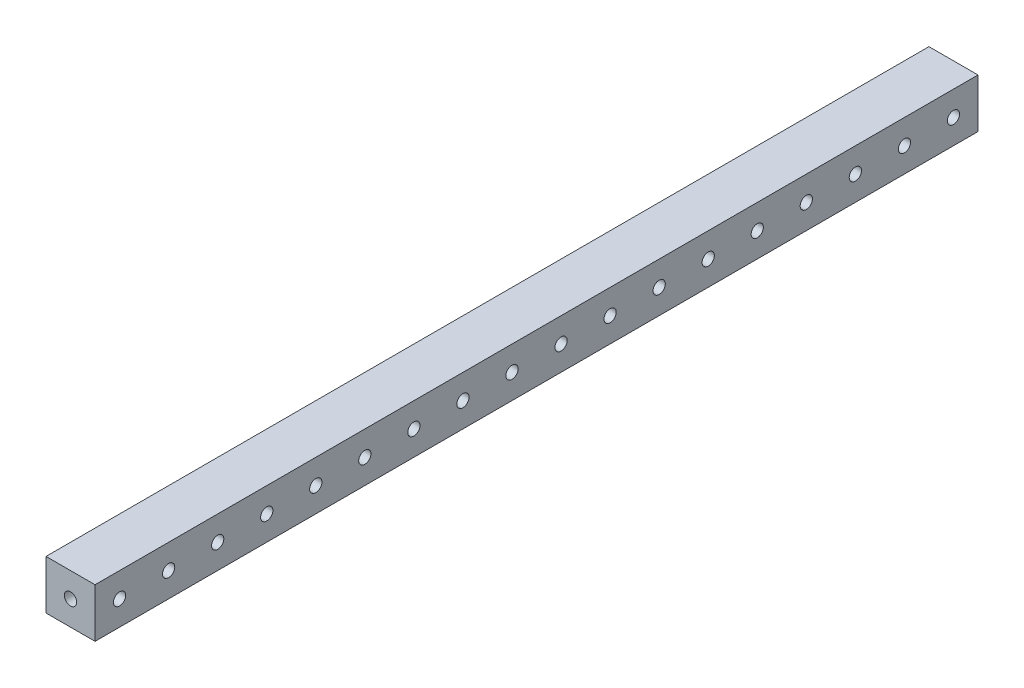
SolidWorks part; units mm, degrees
material "Pine"
ref_plane "Front Plane" through (0, 0, 0) normal (0, 0, 1) x (1, 0, 0)
ref_plane "Top Plane" through (0, 0, 0) normal (0, 1, 0) x (1, 0, 0)
ref_plane "Right Plane" through (0, 0, 0) normal (1, 0, 0) x (0, 0, -1)
sketch "Sketch1" plane through (0, 0, 0) normal (0, 0, 1) x (1, 0, 0)
  line L0 (-10, -10) -> (10, 10) construction
  line L1 (-10, 10) -> (10, 10)
  line L2 (-10, 10) -> (-10, -10)
  line L3 (-10, -10) -> (10, -10)
  line L4 (10, 10) -> (10, -10)
  point P4 (0, 0)
  dimension "D1" = 20
  dimension "D2" = 45
extrude "Boss-Extrude1" add sketch "Sketch1" along normal mid plane 360
hole_wizard "Ø5.0mm Dowel Hole1" positions "Sketch2" profile "Sketch3" hole size "Ø5.0" standard "ANSI Metric" end condition through all
sketch "Sketch2" plane through (10, 0, 0) normal (1, 0, 0) x (0, 0, -1)
  line L0 (180, -10) -> (180, 10) construction
  point P0 (170, 0)
  point P7 (180, 0)
  dimension "D1" = 10
sketch "Sketch3" plane through (10, 0, -170) normal (0, 1, 0) x (0, 0, -1)
  line L0 (0, 0) -> (0, 20)
  line L1 (0, 20) -> (2.5, 20)
  line L2 (2.5, 20) -> (2.5, 0)
  line L5 (2.5, 0) -> (0, 0)
  line L11 (0, -6.35) -> (0, 107.95) construction
  dimension "Thru Hole Dia." = 5
  dimension "Thru Hole Depth" = 20
pattern_linear "LPattern2" count 18 spacing 20 along (0, 0, 1) of "Ø5.0mm Dowel Hole1"
hole_wizard "Ø5.0mm Dowel Hole2" positions "Sketch4" profile "Sketch5" hole size "Ø5.0" standard "ANSI Metric"
sketch "Sketch4" plane through (0, 0, 180) normal (0, 0, 1) x (1, 0, 0)
  point P0 (0, 0)
sketch "Sketch5" plane through (0, 0, 180) normal (1, 0, 0) x (0, -1, 0)
  line L0 (0, 0) -> (0, 21.5022)
  line L1 (0, 21.5022) -> (2.5, 20)
  line L2 (2.5, 20) -> (2.5, 0)
  line L5 (2.5, 0) -> (0, 0)
  line L10 (0, 21.5022) -> (-2.5, 20) construction
  line L11 (0, -6.35) -> (0, 107.95) construction
  dimension "Hole Dia." = 5
  dimension "Hole Depth" = 20
  dimension "Drill Angle" = 118
mirror "Mirror1" about plane through (0, 0, 0) normal (0, 0, 1) of "Ø5.0mm Dowel Hole2"
